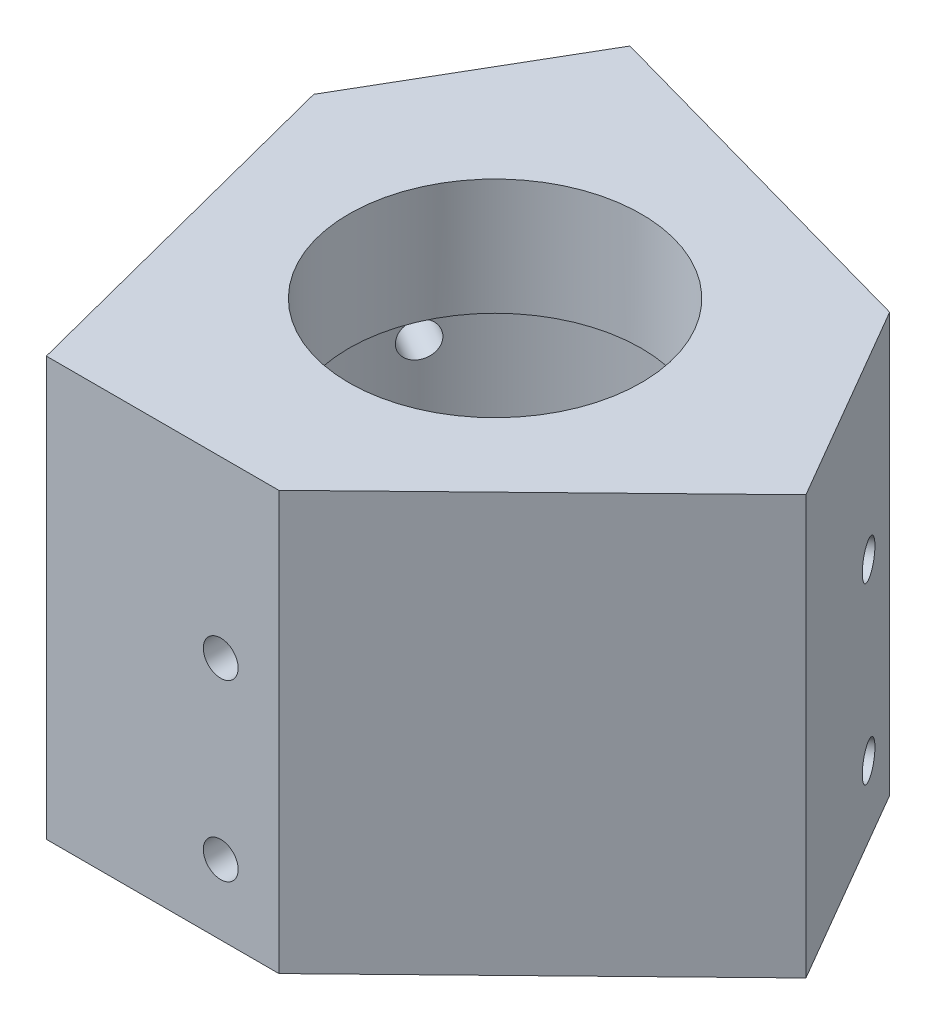
SolidWorks part; units mm, degrees
ref_plane "Front Plane" through (0, 0, 0) normal (0, 0, 1) x (1, 0, 0)
ref_plane "Top Plane" through (0, 0, 0) normal (0, 1, 0) x (1, 0, 0)
ref_plane "Right Plane" through (0, 0, 0) normal (1, 0, 0) x (0, 0, -1)
sketch "Sketch2" plane through (0, 0, 0) normal (0, 1, 0) x (1, 0, 0)
  line L0 (-23, 7.4) -> (-15, -23.6)
  line L1 (-15, -23.6) -> (5, -23.6)
  line L2 (5, -23.6) -> (28, -1.26)
  line L3 (28, -1.26) -> (18, 15.94)
  line L4 (18, 15.94) -> (-13, 24.6)
  line L5 (-13, 24.6) -> (-23, 7.4)
  circle A0 centre (0, 0) radius 12.575
  dimension "D1" = 25.15
  dimension "D2" = 20
  dimension "D3" = 23
  dimension "D4" = 22.34
  dimension "D5" = 8
  dimension "D6" = 31
  dimension "D7" = 23
  dimension "D8" = 7.4
  dimension "D9" = 10
  dimension "D10" = 17.2
  dimension "D11" = 10
  dimension "D12" = 17.2
extrude "Boss-Extrude1" add sketch "Sketch2" against normal blind 36 contours A0 | L1 L2 L3 L4 L5 L0
sketch "Sketch3" plane through (0, -36, 0) normal (0, -1, 0) x (1, 0, 0)
  circle A0 centre (0, 0) radius 17.5
  dimension "D1" = 35
extrude "Cut-Extrude1" cut sketch "Sketch3" against normal blind 26
sketch "Sketch4" plane through (20.3789, 0, -11.8482) normal (0.8645, 0, -0.5026) x (-0.5026, 0, -0.8645)
  line L1 (-15.1627, -36) -> (4.7331, -36) construction
  line L2 (4.7331, -36) -> (4.7331, 0) construction
  circle A0 centre (-0.2669, -15) radius 1.5
  circle A1 centre (-0.2669, -30) radius 1.5
  point P4 (0, 0)
  dimension "D1" = 3
  dimension "D2" = 3
  dimension "D3" = 6
  dimension "D4" = 5
  dimension "D5" = 15
extrude "Cut-Extrude2" cut sketch "Sketch4" against normal up to next
sketch "Sketch7" plane through (-20.405, 0, -11.8634) normal (-0.8645, 0, -0.5026) x (-0.5026, 0, 0.8645)
  line L0 (-14.7328, -36) -> (5.1629, -36) construction
  line L1 (5.1629, -36) -> (5.1629, 0) construction
  circle A0 centre (0.1629, -30) radius 1.5
  circle A1 centre (0.1629, -15) radius 1.5
  point P4 (0, 0)
  dimension "D1" = 3
  dimension "D2" = 3
  dimension "D3" = 6
  dimension "D4" = 5
  dimension "D5" = 15
sketch "Sketch8" plane through (0, 0, 23.6) normal (0, 0, 1) x (1, 0, 0)
  line L0 (-15, -36) -> (5, -36) construction
  line L1 (5, -36) -> (5, 0) construction
  circle A0 centre (0, -30) radius 1.5
  circle A1 centre (0, -15) radius 1.5
  point P4 (0, 0)
  dimension "D1" = 3
  dimension "D2" = 3
  dimension "D3" = 6
  dimension "D4" = 5
  dimension "D5" = 15
extrude "Cut-Extrude5" cut sketch "Sketch7" against normal up to next
extrude "Cut-Extrude6" cut sketch "Sketch8" against normal up to next
